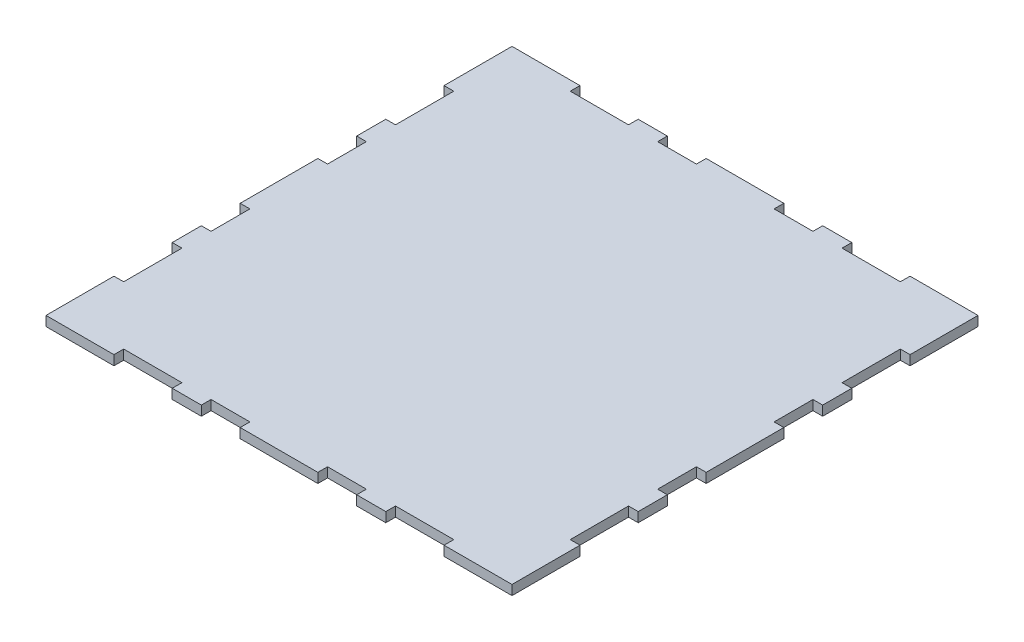
SolidWorks part; units mm, degrees
ref_plane "Front Plane" through (0, 0, 0) normal (0, 0, 1) x (1, 0, 0)
ref_plane "Top Plane" through (0, 0, 0) normal (0, 1, 0) x (1, 0, 0)
ref_plane "Right Plane" through (0, 0, 0) normal (1, 0, 0) x (0, 0, -1)
sketch "Sketch2" plane through (0, 0, 0) normal (0, 1, 0) x (1, 0, 0)
  line L0 (152.4, 0) -> (152.4, 304.8)
  line L1 (0, 0) -> (304.8, 0)
  line L2 (0, 0) -> (0, 304.8)
  line L3 (0, 304.8) -> (304.8, 304.8)
  line L4 (304.8, 0) -> (304.8, 304.8)
  line L5 (101.6, 0) -> (127, 0)
  line L6 (101.6, 0) -> (101.6, 6.35)
  line L7 (101.6, 6.35) -> (127, 6.35)
  line L8 (127, 0) -> (127, 6.35)
  line L9 (44.45, 0) -> (82.55, 0)
  line L10 (44.45, 0) -> (44.45, 6.35)
  line L11 (44.45, 6.35) -> (82.55, 6.35)
  line L12 (82.55, 0) -> (82.55, 6.35)
  line L13 (304.8, 152.4) -> (0, 152.4)
  line L14 (177.8, 0) -> (177.8, 6.35)
  line L15 (203.2, 6.35) -> (177.8, 6.35)
  line L16 (203.2, 0) -> (203.2, 6.35)
  line L17 (222.25, 0) -> (222.25, 6.35)
  line L18 (260.35, 6.35) -> (222.25, 6.35)
  line L19 (260.35, 0) -> (260.35, 6.35)
  line L20 (260.35, 304.8) -> (260.35, 298.45)
  line L21 (260.35, 298.45) -> (222.25, 298.45)
  line L22 (222.25, 304.8) -> (222.25, 298.45)
  line L23 (203.2, 304.8) -> (203.2, 298.45)
  line L24 (203.2, 298.45) -> (177.8, 298.45)
  line L25 (177.8, 304.8) -> (177.8, 298.45)
  line L26 (82.55, 304.8) -> (82.55, 298.45)
  line L27 (44.45, 298.45) -> (82.55, 298.45)
  line L28 (44.45, 304.8) -> (44.45, 298.45)
  line L29 (44.45, 304.8) -> (82.55, 304.8)
  line L30 (127, 304.8) -> (127, 298.45)
  line L31 (101.6, 298.45) -> (127, 298.45)
  line L32 (101.6, 304.8) -> (101.6, 298.45)
  line L33 (101.6, 304.8) -> (127, 304.8)
  line L34 (0, 0) -> (304.8, 304.8)
  line L35 (0, 260.35) -> (6.35, 260.35)
  line L36 (6.35, 260.35) -> (6.35, 222.25)
  line L37 (0, 222.25) -> (6.35, 222.25)
  line L38 (0, 203.2) -> (6.35, 203.2)
  line L39 (6.35, 203.2) -> (6.35, 177.8)
  line L40 (0, 177.8) -> (6.35, 177.8)
  line L41 (0, 82.55) -> (6.35, 82.55)
  line L42 (6.35, 44.45) -> (6.35, 82.55)
  line L43 (0, 44.45) -> (6.35, 44.45)
  line L44 (0, 44.45) -> (0, 82.55)
  line L45 (0, 127) -> (6.35, 127)
  line L46 (6.35, 101.6) -> (6.35, 127)
  line L47 (0, 101.6) -> (6.35, 101.6)
  line L48 (0, 101.6) -> (0, 127)
  line L49 (304.8, 101.6) -> (304.8, 127)
  line L50 (304.8, 101.6) -> (298.45, 101.6)
  line L51 (298.45, 101.6) -> (298.45, 127)
  line L52 (304.8, 127) -> (298.45, 127)
  line L53 (304.8, 44.45) -> (304.8, 82.55)
  line L54 (304.8, 44.45) -> (298.45, 44.45)
  line L55 (298.45, 44.45) -> (298.45, 82.55)
  line L56 (304.8, 82.55) -> (298.45, 82.55)
  line L57 (304.8, 177.8) -> (298.45, 177.8)
  line L58 (298.45, 203.2) -> (298.45, 177.8)
  line L59 (304.8, 203.2) -> (298.45, 203.2)
  line L60 (304.8, 222.25) -> (298.45, 222.25)
  line L61 (298.45, 260.35) -> (298.45, 222.25)
  line L62 (304.8, 260.35) -> (298.45, 260.35)
  point P9 (101.6, 3.175)
  point P14 (44.45, 3.175)
  dimension "D1" = 304.8
  dimension "D2" = 304.8
  dimension "D3" = 6.35
  dimension "D4" = 25.4
  dimension "D5" = 101.6
  dimension "D6" = 6.35
  dimension "D7" = 38.1
  dimension "D8" = 44.45
extrude "Boss-Extrude1" add sketch "Sketch2" along normal blind 6.35 contours L47 L2 L41 L42 L43 L34 L13 L45 L46 | L34 L1 L10 L11 L12 L6 L7 L8 L0 | L56 L4 L50 L51 L52 L13 L0 L1 L14 L15 L16 L17 L18 L19 L54 L55 | L62 L4 L34 L13 L57 L58 L59 L60 L61 | L0 L34 L3 L20 L21 L22 L23 L24 L25 | L40 L2 L13 L0 L3 L30 L31 L32 L26 L27 L28 L35 L36 L37 L38 L39
